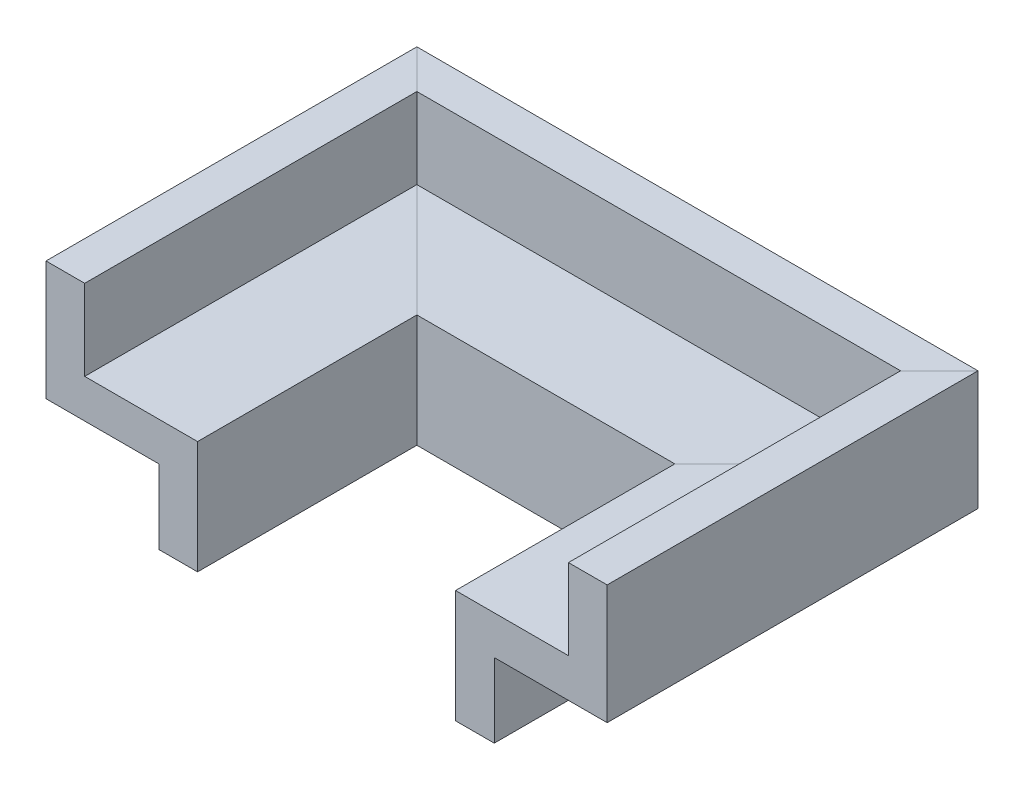
SolidWorks part; units mm, degrees
ref_plane "Front Plane" through (0, 0, 0) normal (0, 0, 1) x (1, 0, 0)
ref_plane "Top Plane" through (0, 0, 0) normal (0, 1, 0) x (1, 0, 0)
ref_plane "Right Plane" through (0, 0, 0) normal (1, 0, 0) x (0, 0, -1)
sketch "Sketch2" plane through (0, 0, 0) normal (0, 1, 0) x (1, 0, 0)
  line L0 (-52, 0) -> (-52, 80)
  line L1 (-52, 80) -> (52, 80)
  line L2 (52, 80) -> (52, 0)
  line L3 (52, 0) -> (52, 80)
  point P3 (0, 0)
  point P6 (0, 80)
  point P8 (0, 0)
  dimension "D1" = 80
  dimension "D2" = 104
sketch "Sketch3" plane through (0, 0, 0) normal (0, 0, 1) x (1, 0, 0)
  line L0 (-52, 0) -> (-87, 0)
  line L1 (-87, 0) -> (-87, 37)
  line L2 (-87, 37) -> (-75, 37)
  line L3 (-75, 37) -> (-75, 12)
  line L4 (-75, 12) -> (-40, 12)
  line L5 (-40, 12) -> (-40, -23)
  line L6 (-40, -23) -> (-52, -23)
  line L7 (-52, -23) -> (-52, 0)
  line L8 (0, -1000) -> (0, 49000) construction
  point P10 (-75, 24.5)
  point P13 (0, 0)
  dimension "D1" = 35
  dimension "D2" = 60
  dimension "D3" = 12
  dimension "D4" = 150
  dimension "D5" = 80
  dimension "D6" = 12
  dimension "D7" = 12
sweep "Sweep1" add profiles "Sketch3" path "Sketch2"
